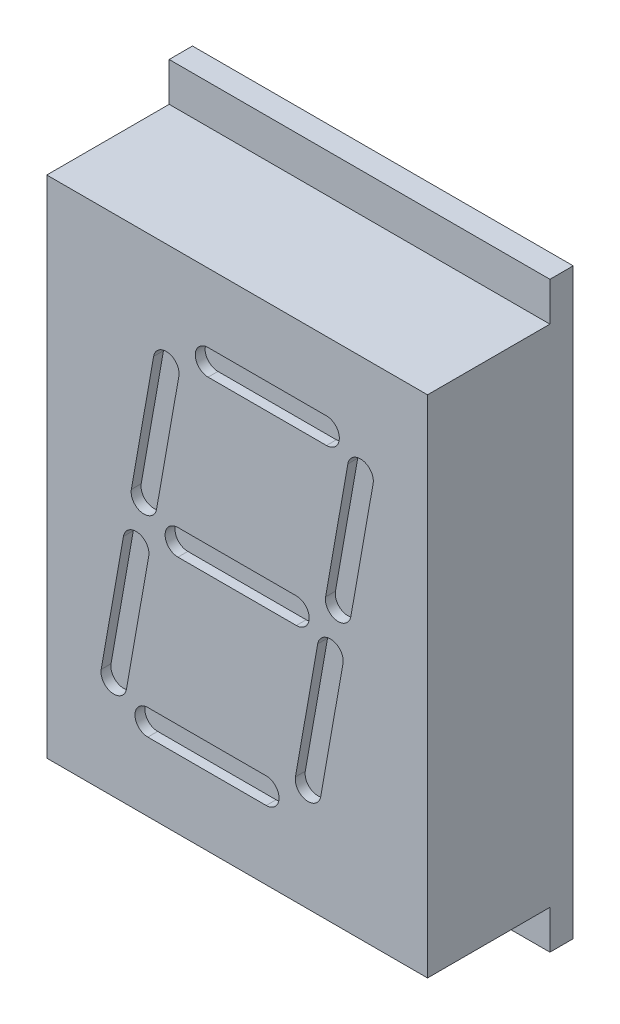
SolidWorks part; units mm, degrees
ref_plane "Front Plane" through (0, 0, 0) normal (0, 0, 1) x (1, 0, 0)
ref_plane "Top Plane" through (0, 0, 0) normal (0, 1, 0) x (1, 0, 0)
ref_plane "Right Plane" through (0, 0, 0) normal (1, 0, 0) x (0, 0, -1)
sketch "Sketch2" plane through (0, 0, 0) normal (0, 0, 1) x (1, 0, 0)
  line L1 (-4.9, 7.5) -> (4.9, 7.5)
  line L2 (-4.9, 7.5) -> (-4.9, -7.5)
  line L3 (-4.9, -7.5) -> (4.9, -7.5)
  line L4 (4.9, 7.5) -> (4.9, -7.5)
  line L5 (-4.9, 7.5) -> (4.9, -7.5) construction
  line L6 (-4.9, -7.5) -> (4.9, 7.5) construction
  point P0 (0, 0)
  dimension "D1" = 15
  dimension "D2" = 9.8
extrude "Boss-Extrude1" add sketch "Sketch2" along normal blind 0.6
sketch "Sketch3" plane through (0, 0, 0.6) normal (0, 0, 1) x (1, 0, 0)
  line L0 (4.9, -7.5) -> (4.9, 7.5) construction
  line L1 (-4.9, 6.5) -> (4.9, 6.5)
  line L2 (-4.9, 6.5) -> (-4.9, -6.5)
  line L3 (-4.9, -6.5) -> (4.9, -6.5)
  line L4 (4.9, 6.5) -> (4.9, -6.5)
  line L5 (-4.9, 6.5) -> (4.9, -6.5) construction
  line L6 (-4.9, -6.5) -> (4.9, 6.5) construction
  point P0 (0, 0)
extrude "Boss-Extrude2" add sketch "Sketch3" along normal blind 3.15
sketch "Sketch4" plane through (0, 0, 3.75) normal (0, 0, 1) x (1, 0, 0)
  line L0 (-4.9, 0) -> (4.9, 0) construction
  line L1 (-4.9, 6.5) -> (-4.9, -6.5) construction
  line L2 (4.9, -6.5) -> (4.9, 6.5) construction
  line L3 (0, 6.5) -> (0, -6.5) construction
  line L4 (4.9, 6.5) -> (-4.9, 6.5) construction
  line L5 (-4.9, -6.5) -> (4.9, -6.5) construction
  line L6 (-4.9, 5) -> (4.9, 5)
  line L7 (-4.9, -5) -> (4.9, -5)
  point P13 (0, 0)
  dimension "D1" = 10
sketch "Sketch5" plane through (0, 0, 3.75) normal (0, 0, 1) x (1, 0, 0)
  line L0 (-4.9, 0) -> (4.9, 0) construction
  line L3 (0, 6.5) -> (0, -6.5) construction
  line L4 (4.9, 6.5) -> (-4.9, 6.5) construction
  line L5 (2.2184, -5) -> (3.9816, 5)
  line L6 (-4.9, 5) -> (4.9, 5) construction
  line L7 (-4.9, -5) -> (4.9, -5) construction
  line L8 (-3.9816, -5) -> (-2.2184, 5)
  line L9 (-3.1, 0) -> (3.1, 0)
  line L10 (-2.2184, 5) -> (3.9816, 5)
  line L11 (-3.9816, -5) -> (2.2184, -5)
  point P0 (3.1, 0)
  point P17 (-3.1, 0)
  dimension "D1" = 3.1
  dimension "D2" = 10
  dimension "D3" = 2
  dimension "D4" = 6.2
sketch "Sketch6" plane through (0, 0, 3.75) normal (0, 0, 1) x (1, 0, 0)
  line L0 (-3.9816, -5) -> (-3.1, 0) construction
  line L1 (-3.1, 0) -> (-2.2184, 5) construction
  line L2 (-2.2184, 5) -> (3.9816, 5) construction
  line L3 (3.9816, 5) -> (3.1, 0) construction
  line L4 (2.2184, -5) -> (3.9816, 5) construction
  line L5 (3.1, 0) -> (2.2184, -5) construction
  line L6 (2.2184, -5) -> (-3.9816, -5) construction
  line L7 (-3.1, 0) -> (3.1, 0) construction
  line L8 (-2.5091, -0.1042) -> (-1.7149, 4.4)
  line L9 (-1.7149, 4.4) -> (3.2666, 4.4)
  line L10 (3.2666, 4.4) -> (2.5091, 0.1042)
  line L11 (2.5091, 0.1042) -> (1.7149, -4.4)
  line L12 (1.7149, -4.4) -> (-3.2666, -4.4)
  line L13 (-3.2666, -4.4) -> (-2.5091, -0.1042)
  dimension "D1" = 0.6
sketch "Sketch8" plane through (0, 0, 3.75) normal (0, 0, 1) x (1, 0, 0)
  line L0 (-1.7149, 4.4) -> (3.2666, 4.4) construction
  line L1 (-2.5091, -0.1042) -> (-1.7149, 4.4) construction
  line L2 (-3.2666, -4.4) -> (-2.5091, -0.1042) construction
  line L3 (1.7149, -4.4) -> (-3.2666, -4.4) construction
  line L4 (2.5091, 0.1042) -> (1.7149, -4.4) construction
  line L5 (3.2666, 4.4) -> (2.5091, 0.1042) construction
  line L6 (-2.3987, 0.522) -> (-1.8253, 3.7738) construction
  line L7 (-2.7239, 0.5793) -> (-2.1505, 3.8312)
  line L8 (-2.0735, 0.4646) -> (-1.5001, 3.7165)
  line L9 (3.1745, 3.878) -> (2.6012, 0.6262) construction
  line L10 (3.4997, 3.8207) -> (2.9263, 0.5688)
  line L11 (2.8494, 3.9354) -> (2.276, 0.6835)
  line L12 (-3.1745, -3.878) -> (-2.6012, -0.6262) construction
  line L13 (-3.4997, -3.8207) -> (-2.9263, -0.5688)
  line L14 (-2.8494, -3.9354) -> (-2.276, -0.6835)
  line L15 (1.8253, -3.7738) -> (2.3987, -0.522) construction
  line L16 (1.5001, -3.7165) -> (2.0735, -0.4646)
  line L17 (2.1505, -3.8312) -> (2.7239, -0.5793)
  line L18 (-2.2998, -4.4) -> (0.7482, -4.4) construction
  line L19 (-2.2998, -4.0698) -> (0.7482, -4.0698)
  line L20 (-2.2998, -4.7302) -> (0.7482, -4.7302)
  line L21 (-1.524, 0) -> (1.524, 0) construction
  line L22 (-3.1, 0) -> (3.1, 0) construction
  line L23 (-1.524, 0.3302) -> (1.524, 0.3302)
  line L24 (-1.524, -0.3302) -> (1.524, -0.3302)
  line L25 (-0.7482, 4.4) -> (2.2998, 4.4) construction
  line L26 (-0.7482, 4.7302) -> (2.2998, 4.7302)
  line L27 (-0.7482, 4.0698) -> (2.2998, 4.0698)
  arc A0 (-2.7239, 0.5793) -> (-2.0735, 0.4646) centre (-2.3987, 0.522) ccw
  arc A1 (-1.5001, 3.7165) -> (-2.1505, 3.8312) centre (-1.8253, 3.7738) ccw
  arc A2 (3.4997, 3.8207) -> (2.8494, 3.9354) centre (3.1745, 3.878) ccw
  arc A3 (2.276, 0.6835) -> (2.9263, 0.5688) centre (2.6012, 0.6262) ccw
  arc A4 (-3.4997, -3.8207) -> (-2.8494, -3.9354) centre (-3.1745, -3.878) ccw
  arc A5 (-2.276, -0.6835) -> (-2.9263, -0.5688) centre (-2.6012, -0.6262) ccw
  arc A6 (1.5001, -3.7165) -> (2.1505, -3.8312) centre (1.8253, -3.7738) ccw
  arc A7 (2.7239, -0.5793) -> (2.0735, -0.4646) centre (2.3987, -0.522) ccw
  arc A8 (-2.2998, -4.0698) -> (-2.2998, -4.7302) centre (-2.2998, -4.4) ccw
  arc A9 (0.7482, -4.7302) -> (0.7482, -4.0698) centre (0.7482, -4.4) ccw
  arc A10 (-1.524, 0.3302) -> (-1.524, -0.3302) centre (-1.524, 0) ccw
  arc A11 (1.524, -0.3302) -> (1.524, 0.3302) centre (1.524, 0) ccw
  arc A12 (-0.7482, 4.7302) -> (-0.7482, 4.0698) centre (-0.7482, 4.4) ccw
  arc A13 (2.2998, 4.0698) -> (2.2998, 4.7302) centre (2.2998, 4.4) ccw
  point P0 (0.7758, 4.4)
  point P1 (-2.112, 2.1479)
  point P4 (-2.8878, -2.2521)
  point P7 (-0.7758, -4.4)
  point P10 (2.112, -2.1479)
  point P13 (2.8878, 2.2521)
  point P16 (0, 0)
  point P22 (-2.112, 2.1479)
  point P29 (2.8878, 2.2521)
  point P35 (-2.8878, -2.2521)
  point P42 (2.112, -2.1479)
  point P49 (-0.7758, -4.4)
  point P56 (0, 0)
  point P65 (0.7758, 4.4)
  dimension "D1" = 0.6604
  dimension "D2" = 3.302
  dimension "D3" = 0.6604
  dimension "D4" = 3.302
  dimension "D5" = 0.6604
  dimension "D6" = 3.302
  dimension "D7" = 0.6604
  dimension "D8" = 3.302
  dimension "D9" = 0.6604
  dimension "D10" = 3.048
  dimension "D11" = 0.6604
  dimension "D12" = 3.048
  dimension "D13" = 0.6604
  dimension "D14" = 3.048
extrude "Cut-Extrude1" cut sketch "Sketch8" against normal blind 0.254
